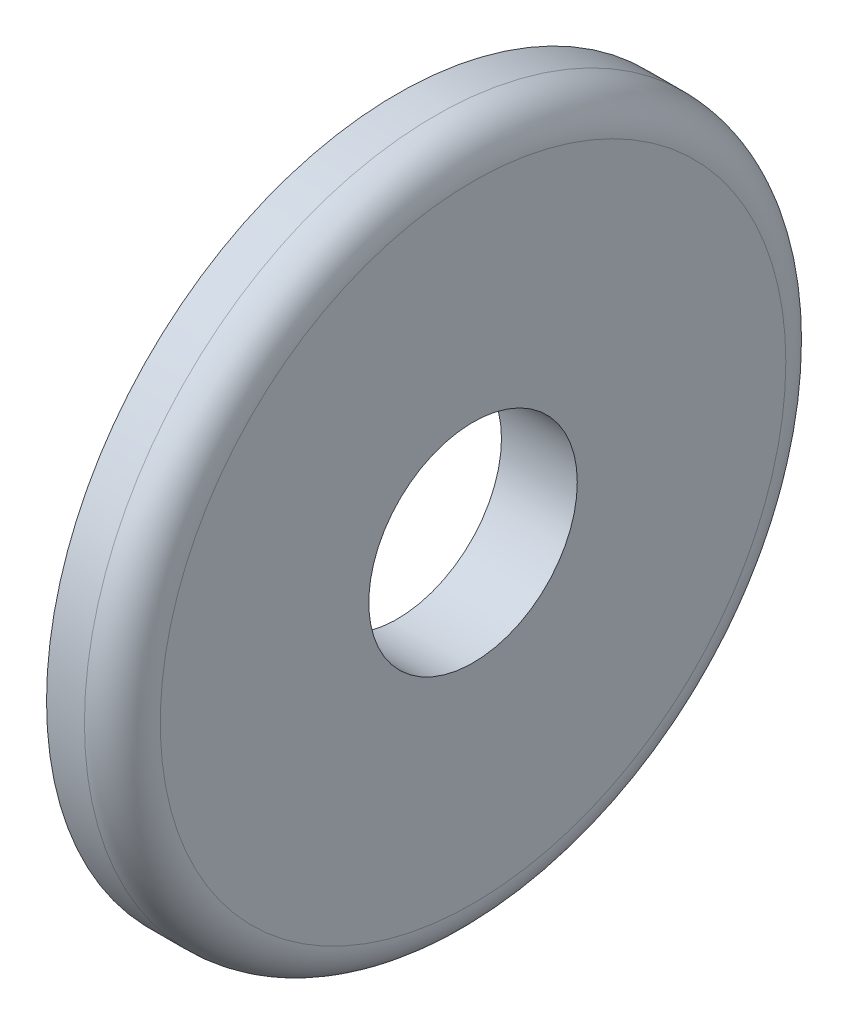
SolidWorks part; units mm, degrees
ref_plane "Płaszczyzna przednia" through (0, 0, 0) normal (0, 0, 1) x (1, 0, 0)
ref_plane "Płaszczyzna górna" through (0, 0, 0) normal (0, 1, 0) x (1, 0, 0)
ref_plane "Płaszczyzna prawa" through (0, 0, 0) normal (1, 0, 0) x (0, 0, -1)
sketch "Szkic1" plane through (0, 0, 0) normal (1, 0, 0) x (0, 0, -1)
  circle A0 centre (0, 0) radius 18.5
  circle A1 centre (0, 0) radius 5.5
  dimension "D1" = 37
  dimension "D2" = 11
extrude "Dodanie-wyciągnięcie1" add sketch "Szkic1" along normal blind 4
fillet "Zaokrąglenie1" radius 2 1 edges at (4, 0, -18.5)
